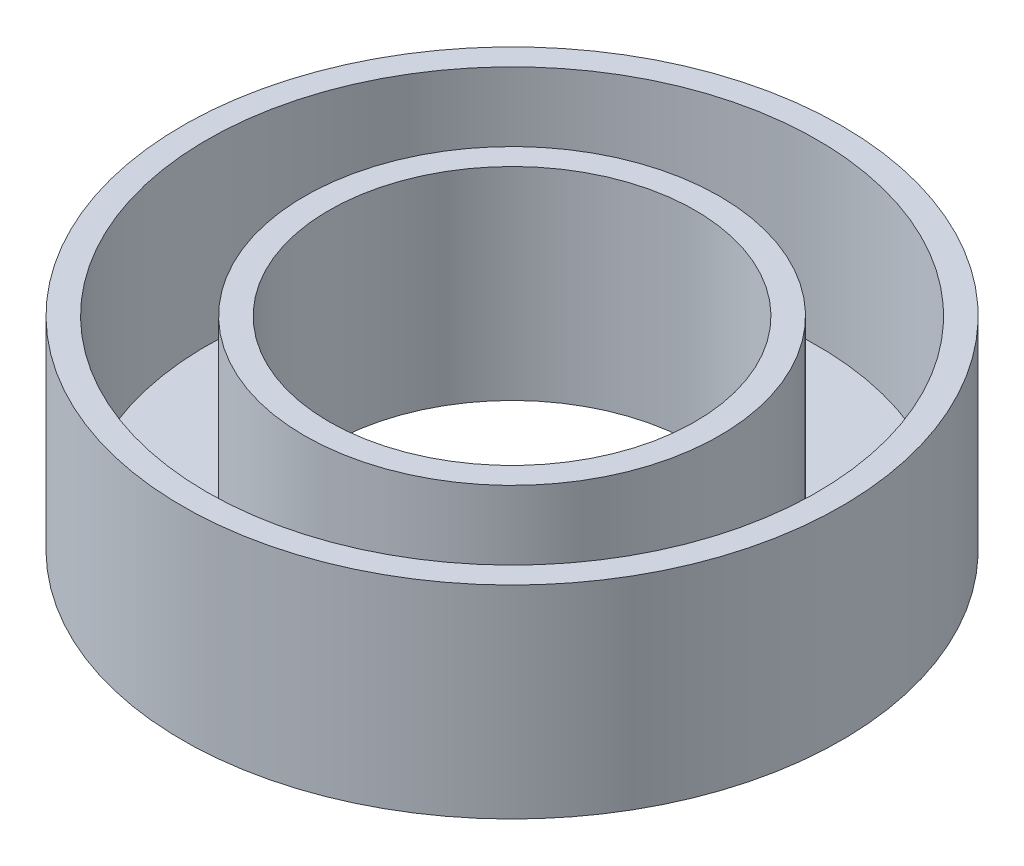
SolidWorks part; units mm, degrees
material "VITON"
ref_plane "Front Plane" through (0, 0, 0) normal (0, 0, 1) x (1, 0, 0)
ref_plane "Top Plane" through (0, 0, 0) normal (0, 1, 0) x (1, 0, 0)
ref_plane "Right Plane" through (0, 0, 0) normal (1, 0, 0) x (0, 0, -1)
sketch "Sketch1" plane through (0, 0, 0) normal (0, 1, 0) x (1, 0, 0)
  circle A0 centre (0, 0) radius 13.5
  dimension "D1" = 27
extrude "main extrusion" add sketch "Sketch1" along normal blind 8.3 contours A0
sketch "Sketch2" plane through (0, 8.3, 0) normal (0, 1, 0) x (1, 0, 0)
  circle A0 centre (0, 0) radius 7.5
  dimension "D1" = 15
extrude "ID bore" cut sketch "Sketch2" against normal blind 20
sketch "Sketch3" plane through (0, 8.3, 0) normal (0, 1, 0) x (1, 0, 0)
  circle A0 centre (0, 0) radius 12.5
  circle A1 centre (0, 0) radius 8.5
  dimension "D1" = 17
  dimension "D2" = 25
extrude "seal recess" cut sketch "Sketch3" against normal blind 7.3
equation "\"D1@Sketch1\" = \"big seal OD\""
equation "\"D1@main extrusion\"=\"big seal depth\""
equation "\"D1@Sketch2\" = \"big seal ID\""
equation "\"motor mount pattern diameter\"= 30mm"
equation "\"D2@Sketch3\" = \"big seal OD\" - 2mm"
equation "\"D1@Sketch3\" = \"big seal ID\" + 2mm"
equation "\"D1@seal recess\" = \"big seal depth\" - 1mm"
equation "\"bearing OD\" = 30mm"
equation "\"bearing outer race thickness\"= 1mm"
equation "\"bearing ID\"= 10mm"
equation "\"bearing depth\"= 9mm"
equation "\"bearing inner race thickness\"= 1mm"
equation "\"small seal OD\" = 20mm"
equation "\"small seal ID\"= 8mm"
equation "\"small seal depth\" = 8.3mm"
equation "\"big seal OD\" = 27mm"
equation "\"big seal ID\"= 15mm"
equation "\"big seal depth\"= 8.3mm"
